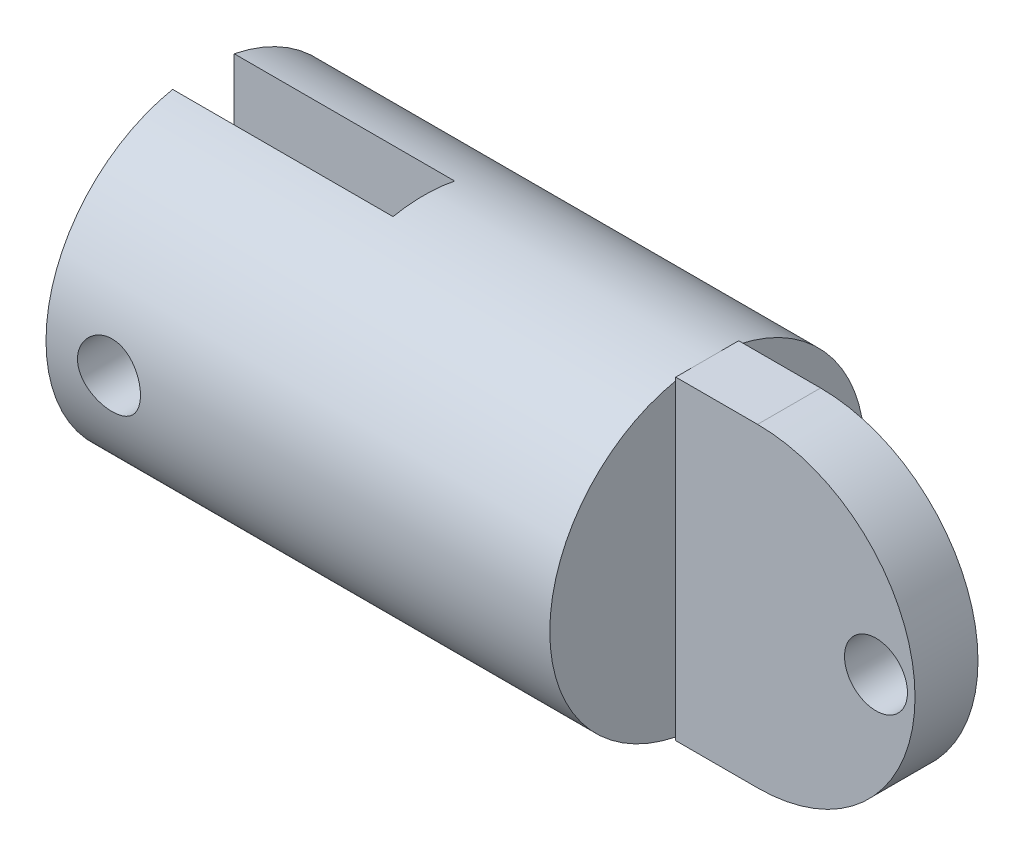
SolidWorks part; units mm, degrees
ref_plane "Front Plane" through (0, 0, 0) normal (0, 0, 1) x (1, 0, 0)
ref_plane "Top Plane" through (0, 0, 0) normal (0, 1, 0) x (1, 0, 0)
ref_plane "Right Plane" through (0, 0, 0) normal (1, 0, 0) x (0, 0, -1)
sketch "Sketch1" plane through (0, 0, 0) normal (1, 0, 0) x (0, 0, -1)
  circle A0 centre (0, 0) radius 12.5
  dimension "D1" = 25
extrude "Boss-Extrude1" add sketch "Sketch1" against normal blind 40
sketch "Sketch6" plane through (0, 0, 0) normal (1, 0, 0) x (0, 0, -1)
  line L0 (-2.5, 12.5) -> (-2.5, -12.5)
  line L1 (-2.5, 12.5) -> (2.5, 12.5)
  line L2 (-2.5, -12.5) -> (2.5, -12.5)
  line L3 (2.5, 12.5) -> (2.5, -12.5)
  line L4 (-2.5, 12.5) -> (2.5, -12.5) construction
  line L5 (-2.5, -12.5) -> (2.5, 12.5) construction
  point P1 (0, 0)
  dimension "D1" = 5
  dimension "D2" = 25
extrude "Boss-Extrude3" add sketch "Sketch6" along normal blind 6.5
sketch "Sketch8" plane through (0, 0, 2.5) normal (0, 0, 1) x (1, 0, 0)
  line L0 (6.5, 12.5) -> (6.5, -12.5) construction
  line L1 (6.5, 12.5) -> (6.5, -12.5)
  arc A0 (6.5, -12.5) -> (6.5, 12.5) centre (6.5, 0) ccw
extrude "Boss-Extrude4" add sketch "Sketch8" against normal blind 5
sketch "Sketch10" plane through (0, 0, 2.5) normal (0, 0, 1) x (1, 0, 0)
  line L0 (0, 12.2474) -> (0, -12.2474) construction
  line L1 (6.5, -12.5) -> (0, -12.5) construction
  circle A0 centre (15.9, 0) radius 2.5
  dimension "D1" = 5
  dimension "D2" = 15.9
  dimension "D3" = 12.5
extrude "Cut-Extrude1" cut sketch "Sketch10" against normal through all and the other way through all
sketch "Sketch12" plane through (-40, 0, 0) normal (-1, 0, 0) x (0, 0, 1)
  line L0 (-2.4468, 12.5) -> (-2.4468, -12.5)
  line L1 (-2.4468, 12.5) -> (2.4468, 12.5)
  line L2 (-2.4468, -12.5) -> (2.4468, -12.5)
  line L3 (2.4468, 12.5) -> (2.4468, -12.5)
  line L4 (-2.4468, 12.5) -> (2.4468, -12.5) construction
  line L5 (-2.4468, -12.5) -> (2.4468, 12.5) construction
  point P1 (0, 0)
extrude "Cut-Extrude2" cut sketch "Sketch12" against normal blind 17.5
sketch "Sketch13" plane through (0, 0, 0) normal (0, 0, 1) x (1, 0, 0)
  line L0 (-40, 12.2582) -> (-40, -12.2582) construction
  line L3 (-22.5, -12.5) -> (0, -12.5) construction
  circle A0 centre (-35, 0) radius 2.5
  point P6 (-33.1247, -12.2582)
  point P7 (-32.4962, -11.3438)
  dimension "D1" = 5
  dimension "D2" = 5
  dimension "D3" = 12.5
extrude "Cut-Extrude3" cut sketch "Sketch13" against normal through all and the other way through all
